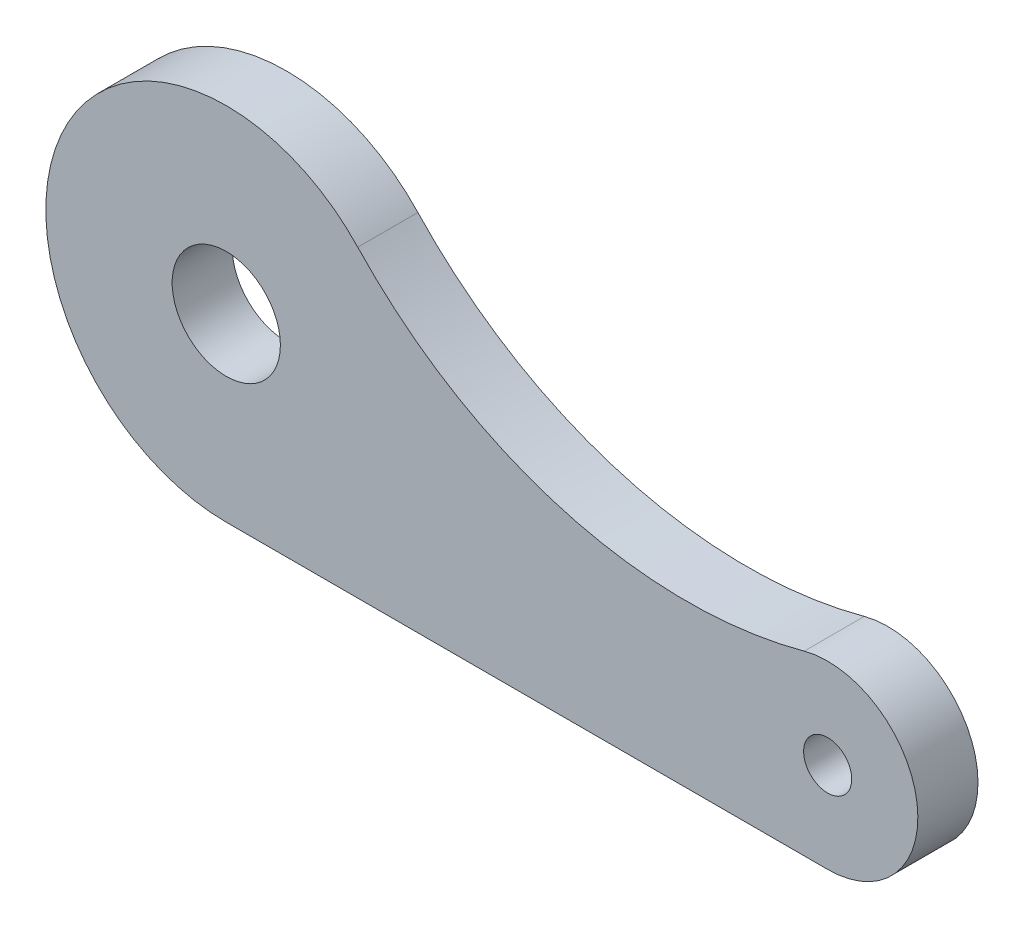
SolidWorks part; units mm, degrees
ref_plane "Piano frontale" through (0, 0, 0) normal (0, 0, 1) x (1, 0, 0)
ref_plane "Piano superiore" through (0, 0, 0) normal (0, 1, 0) x (1, 0, 0)
ref_plane "Piano destro" through (0, 0, 0) normal (1, 0, 0) x (0, 0, -1)
sketch "Schizzo1" plane through (0, 0, 0) normal (0, 0, 1) x (1, 0, 0)
  line L0 (0, -15) -> (50, -15)
  circle A0 centre (0, 0) radius 4.5
  circle A1 centre (50, -7.5) radius 2
  arc A2 (10.9333, 10.2695) -> (0, -15) centre (0, 0) ccw
  arc A3 (50, -15) -> (48.0444, -0.2594) centre (50, -7.5) ccw
  arc A4 (10.9333, 10.2695) -> (48.0444, -0.2594) centre (38.2665, 35.9434) ccw
  dimension "D1" = 9
  dimension "D2" = 4
  dimension "D4" = 30
  dimension "D5" = 15
  dimension "D6" = 75
  dimension "D3" = 50
extrude "Estrusione-Estrusione1" add sketch "Schizzo1" along normal blind 5
